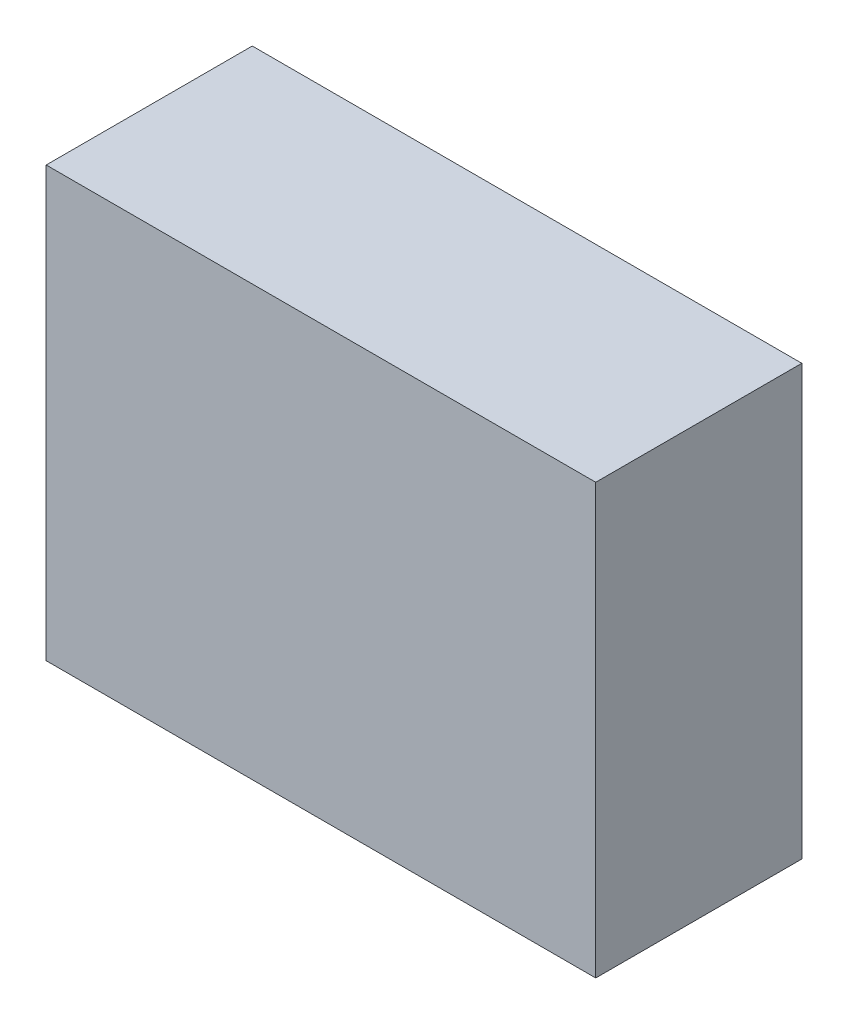
SolidWorks part; units mm, degrees
ref_plane "Front Plane" through (0, 0, 0) normal (0, 0, 1) x (1, 0, 0)
ref_plane "Top Plane" through (0, 0, 0) normal (0, 1, 0) x (1, 0, 0)
ref_plane "Right Plane" through (0, 0, 0) normal (1, 0, 0) x (0, 0, -1)
sketch "Sketch1" plane through (0, 0, 0) normal (0, 0, 1) x (1, 0, 0)
  line L1 (-24, -18.75) -> (24, -18.75)
  line L2 (-24, -18.75) -> (-24, 18.75)
  line L3 (-24, 18.75) -> (24, 18.75)
  line L4 (24, -18.75) -> (24, 18.75)
  line L5 (-24, -18.75) -> (24, 18.75) construction
  line L6 (-24, 18.75) -> (24, -18.75) construction
extrude "Envelope" add sketch "Sketch1" along normal blind 18
